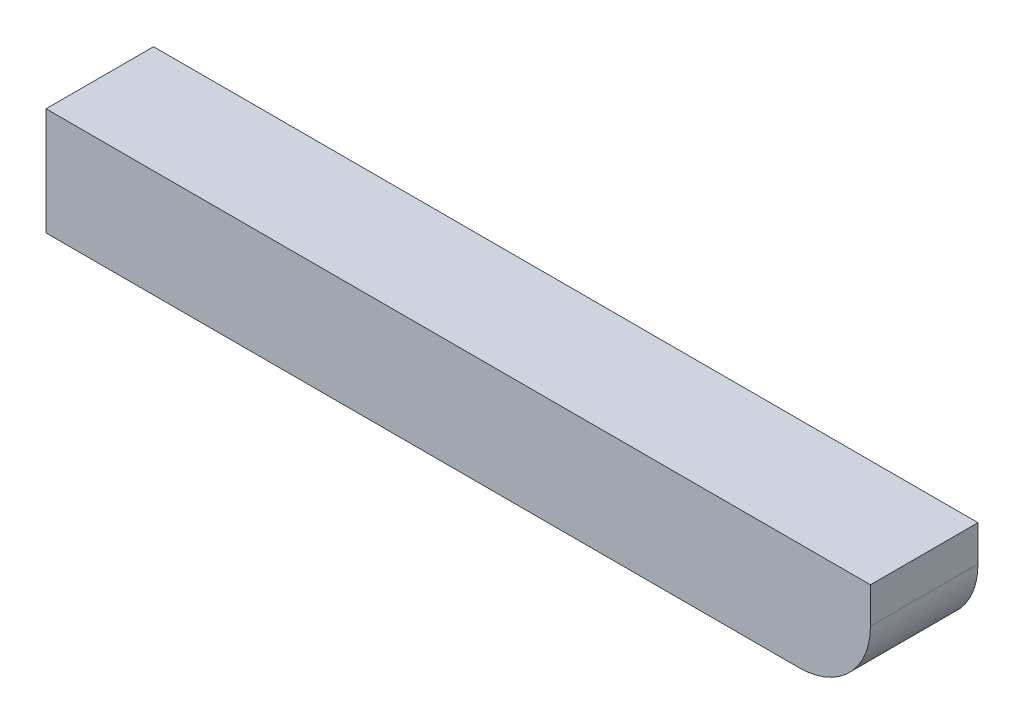
SolidWorks part; units mm, degrees
ref_plane "Piano frontale" through (0, 0, 0) normal (0, 0, 1) x (1, 0, 0)
ref_plane "Piano superiore" through (0, 0, 0) normal (0, 1, 0) x (1, 0, 0)
ref_plane "Piano destro" through (0, 0, 0) normal (1, 0, 0) x (0, 0, -1)
sketch "Schizzo1" plane through (0, 0, 0) normal (0, 0, 1) x (1, 0, 0)
  line L1 (-38.1665, 11.3085) -> (76.8335, 11.3085)
  line L2 (-38.1665, 11.3085) -> (-38.1665, -3.6915)
  line L3 (-38.1665, -3.6915) -> (76.8335, -3.6915)
  line L4 (76.8335, 11.3085) -> (76.8335, -3.6915)
  dimension "D1" = 115
  dimension "D2" = 15
extrude "Estrusione-Estrusione1" add sketch "Schizzo1" along normal blind 15 contours L2 L1 L4 L3
fillet "Raccordo5" radius 10 1 edges at (76.8335, -3.6915, 7.5)
